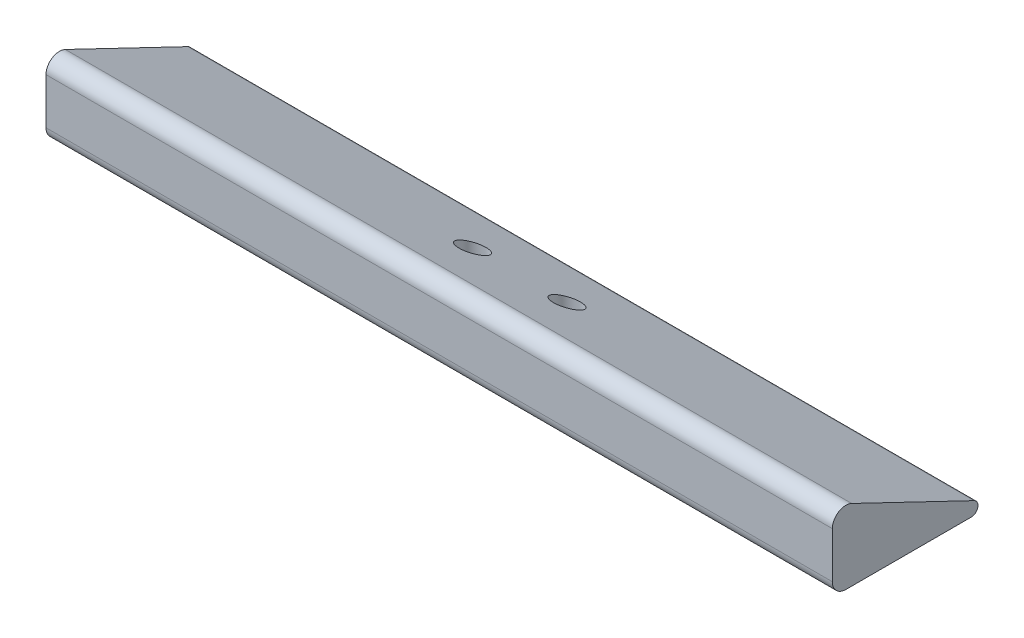
SolidWorks part; units mm, degrees
material "Rubber"
ref_plane "Front Plane" through (0, 0, 0) normal (0, 0, 1) x (1, 0, 0)
ref_plane "Top Plane" through (0, 0, 0) normal (0, 1, 0) x (1, 0, 0)
ref_plane "Right Plane" through (0, 0, 0) normal (1, 0, 0) x (0, 0, -1)
sketch "Sketch1" plane through (0, 0, 0) normal (1, 0, 0) x (0, 0, -1)
  line L0 (2, 0) -> (20.6058, 0)
  line L1 (21.0385, 1.9015) -> (2.8655, 10.6246)
  line L2 (0, 8.8215) -> (0, 2)
  arc A0 (0, 8.8215) -> (2.8655, 10.6246) centre (2, 8.8215) cw
  arc A1 (2, 0) -> (0, 2) centre (2, 2) cw
  arc A2 (21.0385, 1.9015) -> (20.6058, 0) centre (20.6058, 1) cw
  point P6 (0, 12)
  point P9 (0, 0)
  point P12 (25, 0)
  dimension "D1" = 12
  dimension "D3" = 2
  dimension "D4" = 1
  dimension "D2" = 25
extrude "Boss-Extrude1" add sketch "Sketch1" along normal blind 116.65
ref_plane "Plane1" through (0, 10, 0) normal (0, 1, 0) x (1, 0, 0)
sketch "Sketch2" plane through (0, 10, 0) normal (0, 1, 0) x (1, 0, 0)
  line L0 (116.65, 11.952) -> (0, 11.952) construction
  line L1 (116.65, 21.0385) -> (116.65, 2.8655) construction
  line L2 (0, 21.0385) -> (0, 2.8655) construction
  line L3 (58.325, 11.952) -> (58.325, 18.9766) construction
  circle A0 centre (51.325, 11.952) radius 2
  circle A1 centre (65.325, 11.952) radius 2
  dimension "D1" = 4
  dimension "D2" = 7
extrude "Cut-Extrude1" cut sketch "Sketch2" against normal blind 8
sketch "Sketch3" plane through (0, 2, 0) normal (0, 1, 0) x (1, 0, 0)
  circle A0 centre (51.325, 11.952) radius 1.5
  circle A1 centre (65.325, 11.952) radius 1.5
  dimension "D1" = 3
extrude "Cut-Extrude2" cut sketch "Sketch3" against normal through all
